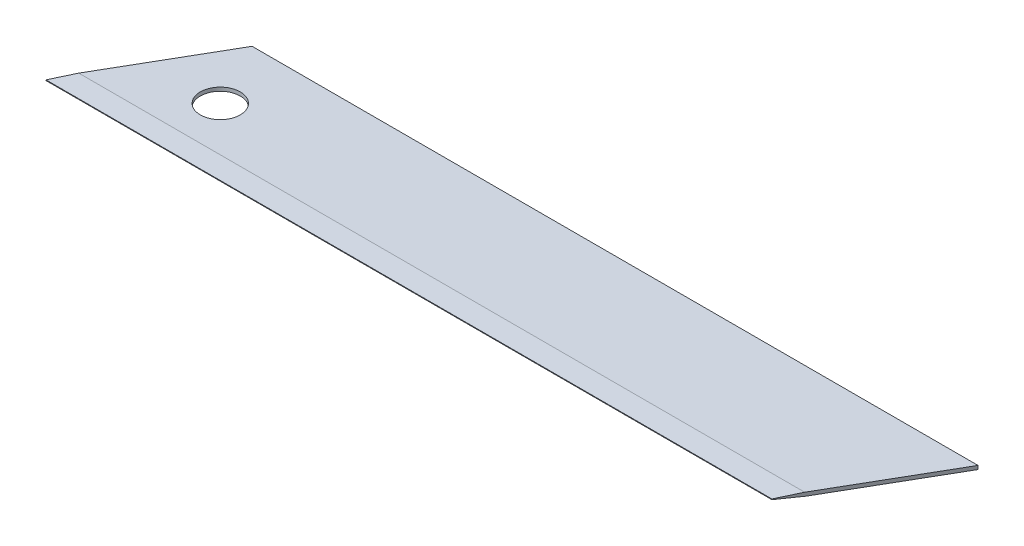
SolidWorks part; units mm, degrees
ref_plane "前视基准面" through (0, 0, 0) normal (0, 0, 1) x (1, 0, 0)
ref_plane "上视基准面" through (0, 0, 0) normal (0, 1, 0) x (1, 0, 0)
ref_plane "右视基准面" through (0, 0, 0) normal (1, 0, 0) x (0, 0, -1)
other "Configuration Table"
sketch "草图1" plane through (0, 0, 0) normal (0, 1, 0) x (1, 0, 0)
  line L0 (0, 0) -> (10.3923, 18)
  line L1 (0, 0) -> (100, 0)
  line L2 (10.3923, 18) -> (110.3923, 18)
  line L3 (100, 0) -> (110.3923, 18)
  dimension "D1" = 120
  dimension "D2" = 0
  dimension "D3" = 100
  dimension "D4" = 18
extrude "凸台-拉伸1" add sketch "草图1" along normal blind 0.5
sketch "草图2" plane through (0, 0, 0) normal (0, -1, 0) x (-1, 0, 0)
  line L0 (-110.3923, 18) -> (-10.3923, 18) construction
  line L3 (-10.3923, 18) -> (0, 0) construction
  circle A0 centre (-15.0111, 9) radius 2.75
  point P6 (-5.7078, 9.8862)
  dimension "D2" = 8.5
  dimension "D3" = 5.5
  dimension "D1" = 9
extrude "切除-拉伸1" cut sketch "草图2" against normal blind 10
chamfer "倒角1" distance 3 angle 4 1 edges at (50, 0, 0)
chamfer "倒角2" distance 0.2 angle 86 1 edges at (50, 0.5, 0)
